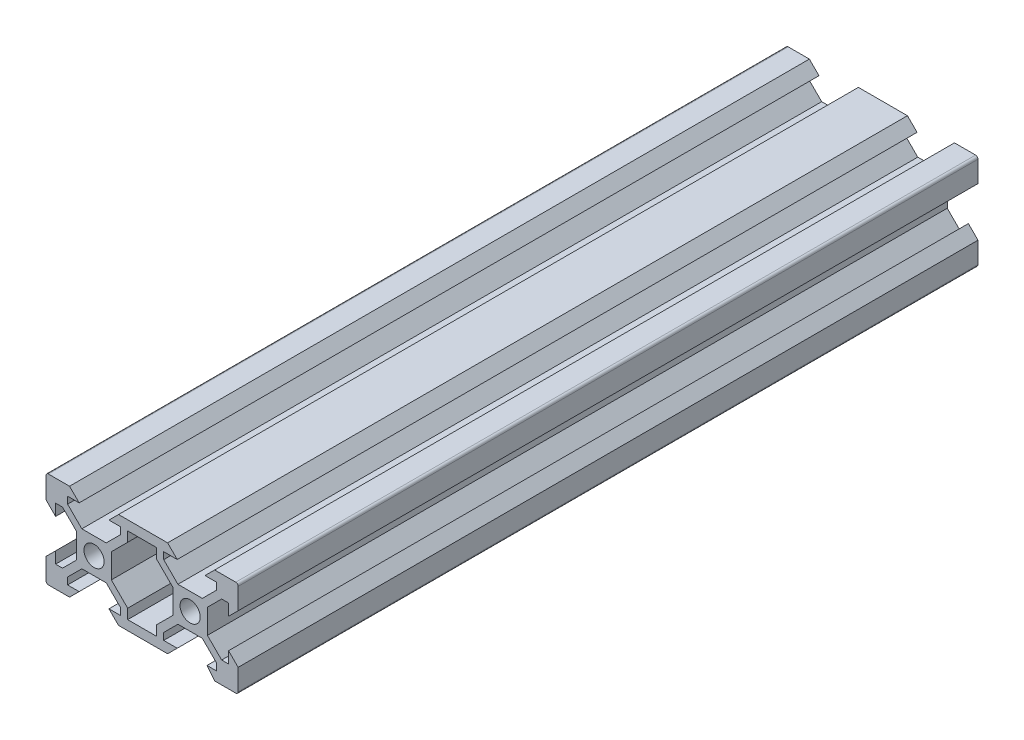
SolidWorks part; units mm, degrees
material "6063-T5"
ref_plane "Front Plane" through (0, 0, 0) normal (0, 0, 1) x (1, 0, 0)
ref_plane "Top Plane" through (0, 0, 0) normal (0, 1, 0) x (1, 0, 0)
ref_plane "Right Plane" through (0, 0, 0) normal (1, 0, 0) x (0, 0, -1)
sketch "Sketch1" plane through (0, 0, 0) normal (0, 0, 1) x (1, 0, 0)
  line L0 (-26.1395, 0) -> (11.0607, 0) construction
  line L1 (0, -20.0817) -> (0, 17.1243) construction
  line L2 (-20, 10.7318) -> (-20, -11.6858) construction
  line L3 (20, 11.8444) -> (20, -11.2237) construction
  line L4 (-23.1467, 10) -> (24.2381, 10) construction
  line L5 (23.8217, -10) -> (-26.7834, -10) construction
  line L6 (3, -5.9393) -> (3, -8)
  line L7 (-20, -10) -> (-15.5, -10)
  line L8 (-20, -10) -> (-20, -5.5)
  line L9 (-18, -5.5) -> (-16.5607, -5.5)
  line L10 (-15.5, -8) -> (-15.5, -6.5607)
  line L11 (-20, 10) -> (-15.5, 10)
  line L12 (-20, 10) -> (-20, 5.5)
  line L13 (-18, 5.5) -> (-16.5607, 5.5)
  line L14 (-15.5, 8) -> (-15.5, 6.5607)
  line L15 (20, 10) -> (15.5, 10)
  line L16 (20, 10) -> (20, 5.5)
  line L17 (18, 5.5) -> (16.5607, 5.5)
  line L18 (15.5, 8) -> (15.5, 6.5607)
  line L19 (20, -10) -> (15.5, -10)
  line L20 (20, -10) -> (20, -5.5)
  line L21 (18, -5.5) -> (16.5607, -5.5)
  line L22 (15.5, -8) -> (15.5, -6.5607)
  line L23 (4.5, -6.5607) -> (4.5, -8)
  line L24 (12.5393, 3.6) -> (15.5, 6.5607)
  line L25 (7.4607, -3.6) -> (4.5, -6.5607)
  line L27 (-4.5, 8) -> (-6.9, 8)
  line L28 (-12.5393, -3.6) -> (-15.5, -6.5607)
  line L29 (7.4607, 3.6) -> (4.5, 6.5607)
  line L30 (12.5393, -3.6) -> (15.5, -6.5607)
  line L31 (-13.6, -2.5393) -> (-16.5607, -5.5)
  line L32 (-13.6, 2.5393) -> (-16.5607, 5.5)
  line L33 (6.4, -2.5393) -> (3, -5.9393)
  line L34 (20, 5.5) -> (20, 5.1)
  line L35 (20, 5.1) -> (18, 3.1)
  line L36 (18, 3.1) -> (18, 5.5)
  line L37 (20, -5.5) -> (20, -5.1)
  line L38 (20, -5.1) -> (18, -3.1)
  line L39 (18, -3.1) -> (18, -5.5)
  line L40 (15.5, 10) -> (15.1, 10)
  line L41 (15.1, 10) -> (13.1, 8)
  line L42 (13.1, 8) -> (15.5, 8)
  line L43 (15.5, -10) -> (15.1, -10)
  line L44 (15.1, -10) -> (13.5138, -8)
  line L45 (13.5138, -8) -> (15.5, -8)
  line L46 (-15.5, 10) -> (-15.1, 10)
  line L47 (-15.1, 10) -> (-13.1, 8)
  line L48 (-13.1, 8) -> (-15.5, 8)
  line L49 (-20, 5.5) -> (-20, 5.1)
  line L50 (-20, 5.1) -> (-18, 3.1)
  line L51 (-18, 3.1) -> (-18, 5.5)
  line L52 (-20, -5.5) -> (-20, -5.1)
  line L53 (-20, -5.1) -> (-18, -3.1)
  line L54 (-18, -3.1) -> (-18, -5.5)
  line L55 (-15.5, -10) -> (-15.1, -10)
  line L56 (-15.1, -10) -> (-13.1, -8)
  line L57 (-13.1, -8) -> (-15.5, -8)
  line L58 (6.4, 2.5393) -> (3, 5.9393)
  line L59 (3, 8) -> (-3, 8)
  line L61 (-3, 5.9393) -> (-3, 8)
  line L62 (-12.5393, 3.6) -> (-15.5, 6.5607)
  line L63 (-4.5, 6.5607) -> (-4.5, 8)
  line L64 (4.5, 6.5607) -> (4.5, 8)
  line L65 (3, 5.9393) -> (3, 8)
  line L66 (13.6, 2.5393) -> (16.5607, 5.5)
  line L67 (12.1, 0) -> (30.0509, 0) construction
  line L68 (-7.4607, 3.6) -> (-4.5, 6.5607)
  line L69 (3, -8) -> (-3, -8)
  line L70 (-6.4, 2.5393) -> (-3, 5.9393)
  line L71 (13.6, -2.5393) -> (16.5607, -5.5)
  line L73 (-3, -5.9393) -> (-3, -8)
  line L74 (-4.5, -6.5607) -> (-4.5, -8)
  line L75 (-7.4607, -3.6) -> (-4.5, -6.5607)
  line L76 (-6.4, -2.5393) -> (-3, -5.9393)
  line L77 (5.3138, -10) -> (7.3138, -8)
  line L78 (7.3138, -8) -> (4.5, -8)
  line L79 (-6.9, -8) -> (-4.9, -10)
  line L80 (-4.9, -10) -> (5.3138, -10)
  line L81 (5.3138, 10) -> (7.3138, 8)
  line L82 (-4.9, 10) -> (5.3138, 10)
  line L83 (-6.9, 8) -> (-4.9, 10)
  line L84 (7.3138, 8) -> (4.5, 8)
  line L85 (7.4607, -3.6) -> (12.5393, -3.6)
  line L86 (-7.4607, -3.6) -> (-12.5393, -3.6)
  line L87 (-6.4, -2.5393) -> (-6.4, 2.5393)
  line L88 (-7.4607, 3.6) -> (-12.5393, 3.6)
  line L89 (-13.6, -2.5393) -> (-13.6, 2.5393)
  line L90 (6.4, -2.5393) -> (6.4, 2.5393)
  line L91 (13.6, -2.5393) -> (13.6, 2.5393)
  line L92 (7.4607, 3.6) -> (12.5393, 3.6)
  line L93 (-4.5, -8) -> (-6.9, -8)
  circle A0 centre (-10, 0) radius 2.1
  circle A1 centre (10, 0) radius 2.1
  dimension "D2" = 4.2
  dimension "D5" = 45
  dimension "D6" = 45
  dimension "D7" = 6.2
  dimension "D8" = 6.2
  dimension "D11" = 3.6
  dimension "D12" = 3.6
  dimension "D38" = 2.4
  dimension "D39" = 45
  dimension "D40" = 2.4
  dimension "D41" = 45
  dimension "D42" = 2
  dimension "D43" = 45
  dimension "D44" = 2.4
  dimension "D45" = 2
  dimension "D49" = 11
extrude "Boss-Extrude1" add sketch "Sketch1" along normal blind 154
fillet "Fillet1" radius 0.5 4 edges at (-20, -10, 77) (-20, 10, 77) (20, -10, 77) (20, 10, 77)
